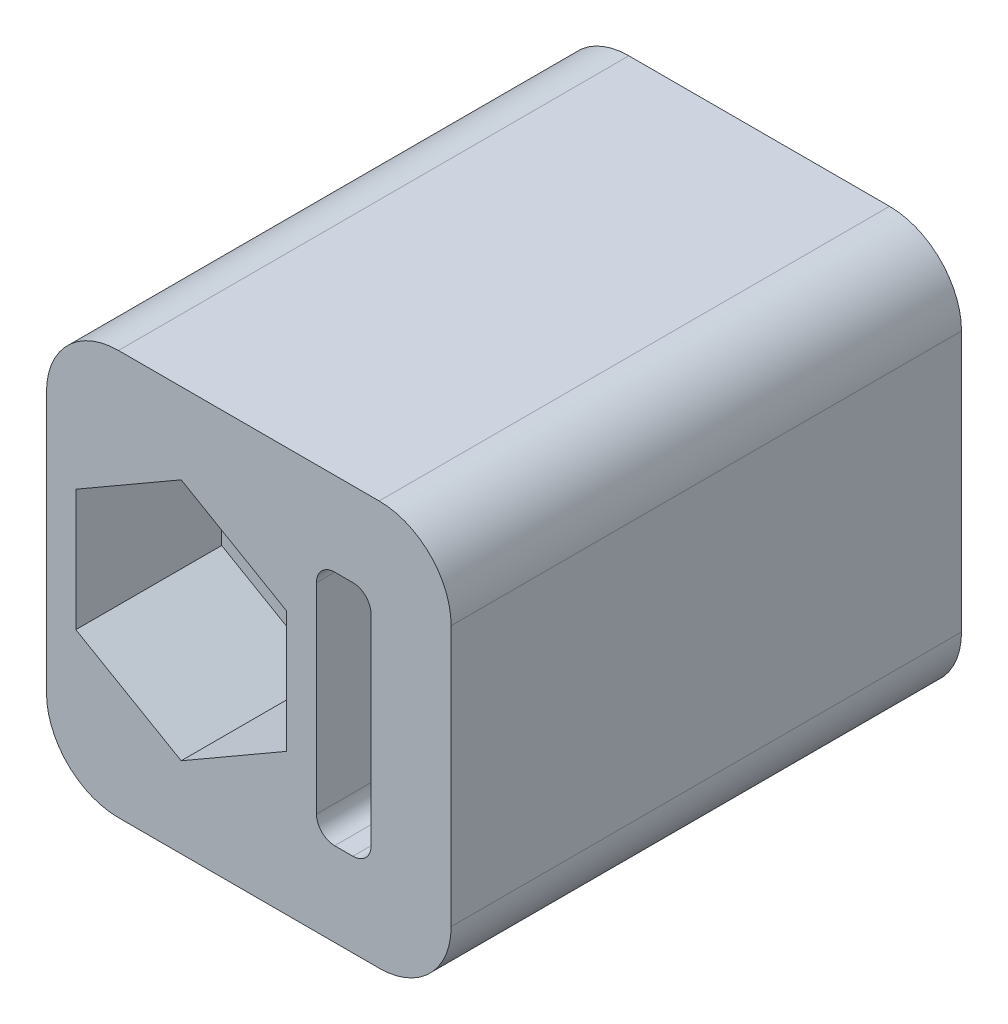
SolidWorks part; units mm, degrees
ref_plane "Front Plane" through (0, 0, 0) normal (0, 0, 1) x (1, 0, 0)
ref_plane "Top Plane" through (0, 0, 0) normal (0, 1, 0) x (1, 0, 0)
ref_plane "Right Plane" through (0, 0, 0) normal (1, 0, 0) x (0, 0, -1)
sketch "Sketch1" plane through (0, 0, 0) normal (0, 0, 1) x (1, 0, 0)
  line L16 (5.21, 2.75) -> (5.21, -2.75)
  line L17 (3.71, 2.75) -> (3.71, -2.75)
  line L18 (4.21, 3.25) -> (4.71, 3.25)
  line L20 (4.21, -3.25) -> (4.71, -3.25)
  line L52 (-3.695, -3.575) -> (-3.695, 3.575)
  line L54 (7.405, -3.575) -> (7.405, 3.575)
  line L55 (5.43, 5.55) -> (-1.72, 5.55)
  line L57 (5.43, -5.55) -> (-1.72, -5.55)
  circle A4 centre (0, 0) radius 1.7
  arc A9 (5.21, -2.75) -> (4.71, -3.25) centre (4.71, -2.75) cw
  arc A14 (4.71, 3.25) -> (5.21, 2.75) centre (4.71, 2.75) cw
  arc A15 (3.71, -2.75) -> (4.21, -3.25) centre (4.21, -2.75) ccw
  arc A16 (3.71, 2.75) -> (4.21, 3.25) centre (4.21, 2.75) cw
  arc A31 (-3.695, -3.575) -> (-1.72, -5.55) centre (-1.72, -3.575) ccw
  arc A33 (-1.72, 5.55) -> (-3.695, 3.575) centre (-1.72, 3.575) ccw
  arc A35 (5.43, -5.55) -> (7.405, -3.575) centre (5.43, -3.575) ccw
  arc A37 (7.405, 3.575) -> (5.43, 5.55) centre (5.43, 3.575) ccw
extrude "Boss-Extrude1" add sketch "Sketch1" along normal blind 14
sketch "Sketch2" plane through (0, 0, 14) normal (0, 0, 1) x (1, 0, 0)
  line L19 (0, 3.3371) -> (-2.89, 1.6685)
  line L20 (-2.89, 1.6685) -> (-2.89, -1.6685)
  line L21 (-2.89, -1.6685) -> (0, -3.3371)
  line L22 (0, -3.3371) -> (2.89, -1.6685)
  line L23 (2.89, -1.6685) -> (2.89, 1.6685)
  line L24 (2.89, 1.6685) -> (0, 3.3371)
extrude "Cut-Extrude1" cut sketch "Sketch2" against normal blind 4
sketch "Sketch3" plane through (0, 0, 0) normal (0, 0, 1) x (1, 0, 0)
  line L0 (3.71, 2.75) -> (3.71, -2.75)
  line L2 (6.01, 2.75) -> (6.01, -2.75)
  line L4 (5.51, -3.25) -> (4.21, -3.25)
  line L6 (4.21, 3.25) -> (5.51, 3.25)
  arc A0 (6.01, 2.75) -> (5.51, 3.25) centre (5.51, 2.75) ccw
  arc A1 (5.51, -3.25) -> (6.01, -2.75) centre (5.51, -2.75) ccw
  arc A2 (3.71, -2.75) -> (4.21, -3.25) centre (4.21, -2.75) ccw
  arc A5 (4.21, 3.25) -> (3.71, 2.75) centre (4.21, 2.75) ccw
extrude "Cut-Extrude2" cut sketch "Sketch3" along normal blind 7
